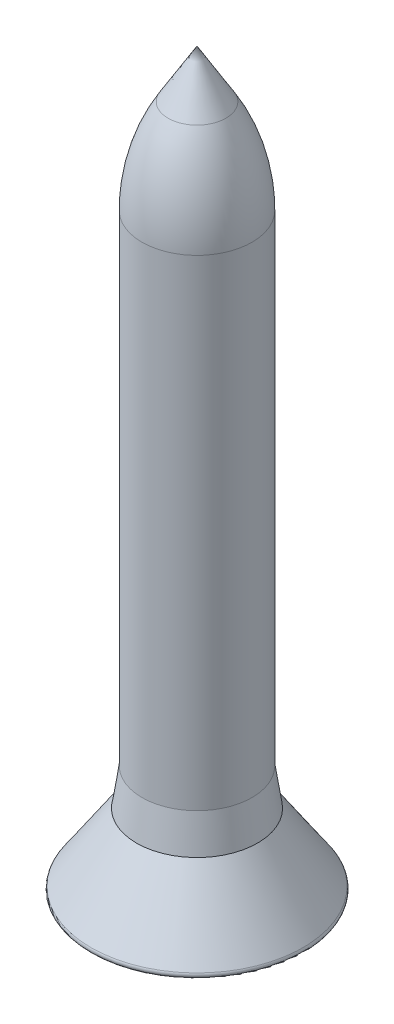
SolidWorks part; units mm, degrees
ref_plane "Alzado" through (0, 0, 0) normal (0, 0, 1) x (1, 0, 0)
ref_plane "Planta" through (0, 0, 0) normal (0, 1, 0) x (1, 0, 0)
ref_plane "Vista lateral" through (0, 0, 0) normal (1, 0, 0) x (0, 0, -1)
sketch "Croquis1" plane through (0, 0, 0) normal (0, 0, 1) x (1, 0, 0)
  line L0 (0, 0) -> (3, 0)
  line L1 (3, 0) -> (1.65, 2)
  line L5 (0, 20) -> (0, 0)
  line L6 (0, 0) -> (0, -32505.4588) construction
  line L7 (1.65, 2) -> (1.5, 3)
  line L8 (1.5, 3) -> (1.5, 16.1151)
  line L10 (0.7875, 18.6876) -> (0, 20)
  arc A1 (1.5, 16.1151) -> (0.7875, 18.6876) centre (-3.5, 16.1151) ccw
  point P6 (1.5, 17.5)
  dimension "D8" = 5
  dimension "D1" = 6
  dimension "D2" = 2
  dimension "D3" = 3
  dimension "D4" = 3.3
  dimension "D5" = 1
  dimension "D6" = 20
  dimension "D7" = 2.5
revolve "Revolución1" add sketch "Croquis1" angle 360 about L6
sketch "Croquis2" plane through (0, 0, 0) normal (0, -1, 0) x (1, 0, 0)
  line L0 (0, 1.8) -> (0, -1.8)
  line L1 (-1.8, 0) -> (1.8, 0)
  point P4 (0, 0)
  point P8 (0, 0)
  dimension "D1" = 3.6
extrude "Cortar-Extruir-Lámina1" cut sketch "Croquis2" against normal blind 2 draft 15 thin thin type mid plane wall 0.6
fillet "Redondeo1" radius 0.1 1 edges at (0, 0, 3)
